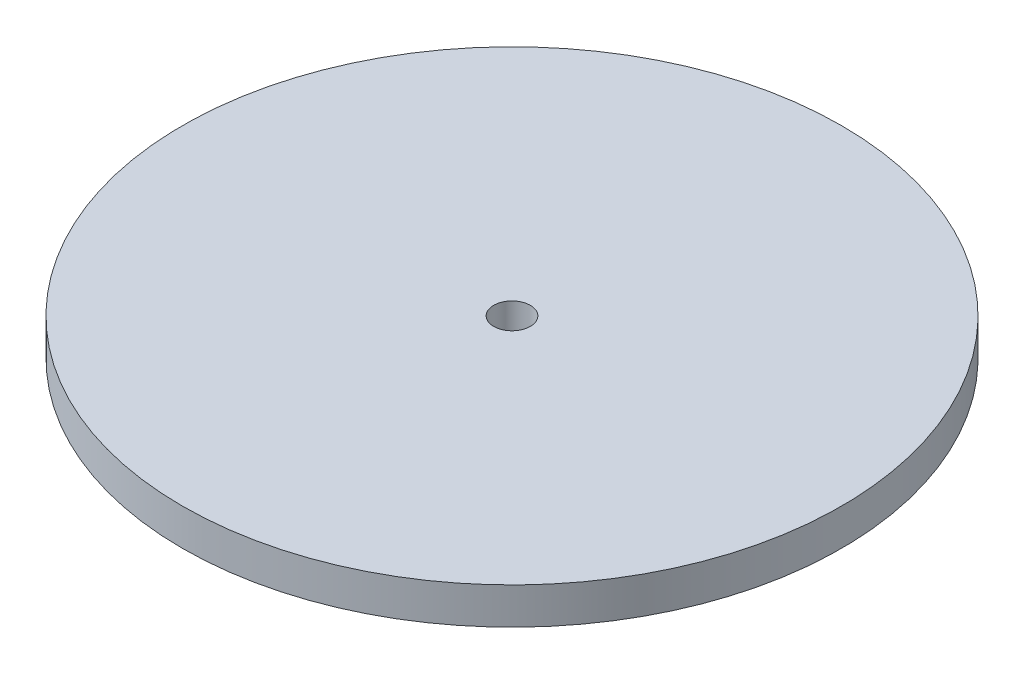
SolidWorks part; units mm, degrees
ref_plane "Front Plane" through (0, 0, 0) normal (0, 0, 1) x (1, 0, 0)
ref_plane "Top Plane" through (0, 0, 0) normal (0, 1, 0) x (1, 0, 0)
ref_plane "Right Plane" through (0, 0, 0) normal (1, 0, 0) x (0, 0, -1)
sketch "Sketch1" plane through (0, 0, 0) normal (0, 1, 0) x (1, 0, 0)
  circle A0 centre (0, 0) radius 45
  circle A1 centre (0, 0) radius 2.5
  dimension "D1" = 90
  dimension "D2" = 5
extrude "Boss-Extrude1" add sketch "Sketch1" along normal blind 5
